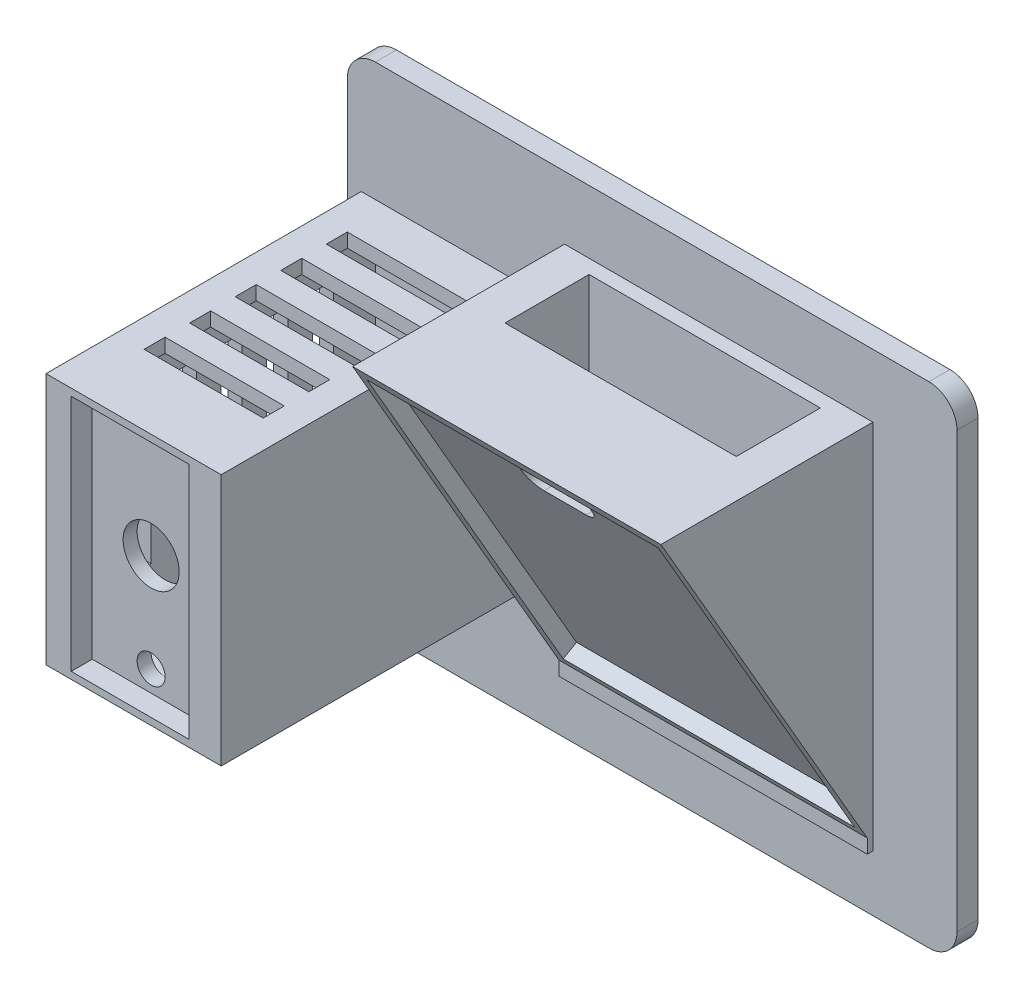
SolidWorks part; units mm, degrees
ref_plane "Front Plane" through (0, 0, 0) normal (0, 0, 1) x (1, 0, 0)
ref_plane "Top Plane" through (0, 0, 0) normal (0, 1, 0) x (1, 0, 0)
ref_plane "Right Plane" through (0, 0, 0) normal (1, 0, 0) x (0, 0, -1)
ref_plane "Plane_Z+373.20" through (0, 0, 373.2) normal (0, 0, 1) x (1, 0, 0)
sketch "Sketch1" plane through (0, 0, 373.2) normal (0, 0, 1) x (1, 0, 0)
  line L0 (-131, -35) -> (-52, -35)
  line L1 (-48, -31) -> (-48, 31)
  line L2 (-52, 35) -> (-131, 35)
  line L3 (-135, 31) -> (-135, -31)
  arc A0 (-52, -35) -> (-48, -31) centre (-52, -31) ccw
  arc A1 (-48, 31) -> (-52, 35) centre (-52, 31) ccw
  arc A2 (-131, 35) -> (-135, 31) centre (-131, 31) ccw
  arc A3 (-135, -31) -> (-131, -35) centre (-131, -31) ccw
extrude "Base_plate" add sketch "Sketch1" along normal blind 3
ref_plane "Plane_X-104.00" through (-104, 0, 0) normal (1, 0, 0) x (0, 0, -1)
sketch "Sketch2" plane through (-104, 0, 0) normal (1, 0, 0) x (0, 0, -1)
  line L0 (-376.19, -27) -> (-376.19, 26)
  line L1 (-376.19, 26) -> (-406.4449, 26)
  line L2 (-406.4449, 26) -> (-377, -25)
  line L3 (-377, -25) -> (-377, -27)
  line L4 (-377, -27) -> (-376.19, -27)
extrude "Rain_plate_wedge" add sketch "Sketch2" along normal blind 44
ref_plane "Plane_X-82.00" through (-82, 0, 0) normal (1, 0, 0) x (0, 0, -1)
sketch "Sketch3" plane through (-82, 0, 0) normal (1, 0, 0) x (0, 0, -1)
  line L0 (-377.8598, -24.1108) -> (-405.8598, 24.3867)
  line L1 (-405.8598, 24.3867) -> (-403.6947, 25.6367)
  line L2 (-403.6947, 25.6367) -> (-375.6947, -22.8608)
  line L3 (-375.6947, -22.8608) -> (-377.8598, -24.1108)
extrude "Rain_plate_pocket" cut sketch "Sketch3" against normal mid plane 41.6
ref_plane "Plane_Y+17.50" through (0, 17.5, 0) normal (0, 1, 0) x (1, 0, 0)
sketch "Sketch4" plane through (0, 17.5, 0) normal (0, 1, 0) x (1, 0, 0)
  line L0 (-98.5, -378.2) -> (-65.5, -378.2)
  line L1 (-65.5, -378.2) -> (-65.5, -390.2)
  line L2 (-65.5, -390.2) -> (-98.5, -390.2)
  line L3 (-98.5, -390.2) -> (-98.5, -378.2)
extrude "LM393_board_pocket" cut sketch "Sketch4" against normal mid plane 19
ref_plane "Plane_Z+404.70" through (0, 0, 404.7) normal (0, 0, 1) x (1, 0, 0)
sketch "Sketch5" plane through (0, 0, 404.7) normal (0, 0, 1) x (1, 0, 0)
  line L0 (-85, 16) -> (-79, 16)
  line L1 (-77, 18) -> (-77, 22)
  line L2 (-79, 24) -> (-85, 24)
  line L3 (-87, 22) -> (-87, 18)
  arc A0 (-79, 16) -> (-77, 18) centre (-79, 18) ccw
  arc A1 (-77, 22) -> (-79, 24) centre (-79, 22) ccw
  arc A2 (-85, 24) -> (-87, 22) centre (-85, 22) ccw
  arc A3 (-87, 18) -> (-85, 16) centre (-85, 18) ccw
extrude "Rain_plate_pin_hole" cut sketch "Sketch5" against normal mid plane 30
ref_plane "Plane_Z+376.20" through (0, 0, 376.2) normal (0, 0, 1) x (1, 0, 0)
sketch "Sketch6" plane through (0, 0, 376.2) normal (0, 0, 1) x (1, 0, 0)
  line L0 (-133, -18) -> (-108, -18)
  line L1 (-108, -18) -> (-108, 18)
  line L2 (-108, 18) -> (-133, 18)
  line L3 (-133, 18) -> (-133, -18)
  line L4 (-131, -16) -> (-110, -16)
  line L5 (-110, -16) -> (-110, 16)
  line L6 (-110, 16) -> (-131, 16)
  line L7 (-131, 16) -> (-131, -16)
extrude "DHT11_screen_walls" add sketch "Sketch6" along normal blind 40
ref_plane "Plane_Z+416.20" through (0, 0, 416.2) normal (0, 0, 1) x (1, 0, 0)
sketch "Sketch7" plane through (0, 0, 416.2) normal (0, 0, 1) x (1, 0, 0)
  line L0 (-133, -18) -> (-108, -18)
  line L1 (-108, -18) -> (-108, 18)
  line L2 (-108, 18) -> (-133, 18)
  line L3 (-133, 18) -> (-133, -18)
extrude "DHT11_screen_roof" add sketch "Sketch7" along normal blind 5
ref_plane "Plane_Z+419.95" through (0, 0, 419.95) normal (0, 0, 1) x (1, 0, 0)
sketch "Sketch8" plane through (0, 0, 419.95) normal (0, 0, 1) x (1, 0, 0)
  line L0 (-129.4, -17) -> (-112.6, -17)
  line L1 (-112.6, -17) -> (-112.6, 17)
  line L2 (-112.6, 17) -> (-129.4, 17)
  line L3 (-129.4, 17) -> (-129.4, -17)
extrude "LDR_module_pocket" cut sketch "Sketch8" against normal mid plane 3.5
ref_plane "Plane_Z+417.20" through (0, 0, 417.2) normal (0, 0, 1) x (1, 0, 0)
sketch "Sketch9" plane through (0, 0, 417.2) normal (0, 0, 1) x (1, 0, 0)
  circle A0 centre (-121, -14) radius 2
  circle A1 centre (-121, 0) radius 4
extrude "LDR_and_screen_wire_holes" cut sketch "Sketch9" against normal mid plane 3
ref_plane "Plane_Z+374.70" through (0, 0, 374.7) normal (0, 0, 1) x (1, 0, 0)
sketch "Sketch10" plane through (0, 0, 374.7) normal (0, 0, 1) x (1, 0, 0)
  circle A0 centre (-121, 0) radius 4
extrude "DHT11_wire_hole" cut sketch "Sketch10" against normal mid plane 4
ref_plane "Plane_Z+374.25" through (0, 0, 374.25) normal (0, 0, 1) x (1, 0, 0)
sketch "Sketch11" plane through (0, 0, 374.25) normal (0, 0, 1) x (1, 0, 0)
  circle A0 centre (-90, 20) radius 1
  circle A1 centre (-90, -20) radius 1
extrude "Filament_pin_holes" cut sketch "Sketch11" against normal mid plane 3.1
ref_plane "Plane_X-132.00" through (-132, 0, 0) normal (1, 0, 0) x (0, 0, -1)
sketch "Sketch12" plane through (-132, 0, 0) normal (1, 0, 0) x (0, 0, -1)
  line L0 (-382.2, -11) -> (-382.2, 11)
  line L1 (-382.2, 11) -> (-385.2, 11)
  line L2 (-385.2, 11) -> (-385.2, -11)
  line L3 (-385.2, -11) -> (-382.2, -11)
  line L4 (-388.7, -11) -> (-388.7, 11)
  line L5 (-388.7, 11) -> (-391.7, 11)
  line L6 (-391.7, 11) -> (-391.7, -11)
  line L7 (-391.7, -11) -> (-388.7, -11)
  line L8 (-395.2, -11) -> (-395.2, 11)
  line L9 (-395.2, 11) -> (-398.2, 11)
  line L10 (-398.2, 11) -> (-398.2, -11)
  line L11 (-398.2, -11) -> (-395.2, -11)
  line L12 (-401.7, -11) -> (-401.7, 11)
  line L13 (-401.7, 11) -> (-404.7, 11)
  line L14 (-404.7, 11) -> (-404.7, -11)
  line L15 (-404.7, -11) -> (-401.7, -11)
  line L16 (-408.2, -11) -> (-408.2, 11)
  line L17 (-408.2, 11) -> (-411.2, 11)
  line L18 (-411.2, 11) -> (-411.2, -11)
  line L19 (-411.2, -11) -> (-408.2, -11)
extrude "Louvres_back" cut sketch "Sketch12" against normal mid plane 4
ref_plane "Plane_Y+17.00" through (0, 17, 0) normal (0, 1, 0) x (1, 0, 0)
sketch "Sketch13" plane through (0, 17, 0) normal (0, 1, 0) x (1, 0, 0)
  line L0 (-129, -382.2) -> (-112, -382.2)
  line L1 (-112, -382.2) -> (-112, -385.2)
  line L2 (-112, -385.2) -> (-129, -385.2)
  line L3 (-129, -385.2) -> (-129, -382.2)
  line L4 (-129, -388.7) -> (-112, -388.7)
  line L5 (-112, -388.7) -> (-112, -391.7)
  line L6 (-112, -391.7) -> (-129, -391.7)
  line L7 (-129, -391.7) -> (-129, -388.7)
  line L8 (-129, -395.2) -> (-112, -395.2)
  line L9 (-112, -395.2) -> (-112, -398.2)
  line L10 (-112, -398.2) -> (-129, -398.2)
  line L11 (-129, -398.2) -> (-129, -395.2)
  line L12 (-129, -401.7) -> (-112, -401.7)
  line L13 (-112, -401.7) -> (-112, -404.7)
  line L14 (-112, -404.7) -> (-129, -404.7)
  line L15 (-129, -404.7) -> (-129, -401.7)
  line L16 (-129, -408.2) -> (-112, -408.2)
  line L17 (-112, -408.2) -> (-112, -411.2)
  line L18 (-112, -411.2) -> (-129, -411.2)
  line L19 (-129, -411.2) -> (-129, -408.2)
extrude "Louvres_stbd" cut sketch "Sketch13" against normal mid plane 4
ref_plane "Plane_Y-17.00" through (0, -17, 0) normal (0, 1, 0) x (1, 0, 0)
sketch "Sketch14" plane through (0, -17, 0) normal (0, 1, 0) x (1, 0, 0)
  line L0 (-129, -382.2) -> (-112, -382.2)
  line L1 (-112, -382.2) -> (-112, -385.2)
  line L2 (-112, -385.2) -> (-129, -385.2)
  line L3 (-129, -385.2) -> (-129, -382.2)
  line L4 (-129, -388.7) -> (-112, -388.7)
  line L5 (-112, -388.7) -> (-112, -391.7)
  line L6 (-112, -391.7) -> (-129, -391.7)
  line L7 (-129, -391.7) -> (-129, -388.7)
  line L8 (-129, -395.2) -> (-112, -395.2)
  line L9 (-112, -395.2) -> (-112, -398.2)
  line L10 (-112, -398.2) -> (-129, -398.2)
  line L11 (-129, -398.2) -> (-129, -395.2)
  line L12 (-129, -401.7) -> (-112, -401.7)
  line L13 (-112, -401.7) -> (-112, -404.7)
  line L14 (-112, -404.7) -> (-129, -404.7)
  line L15 (-129, -404.7) -> (-129, -401.7)
  line L16 (-129, -408.2) -> (-112, -408.2)
  line L17 (-112, -408.2) -> (-112, -411.2)
  line L18 (-112, -411.2) -> (-129, -411.2)
  line L19 (-129, -411.2) -> (-129, -408.2)
extrude "Louvres_port" cut sketch "Sketch14" against normal mid plane 4
